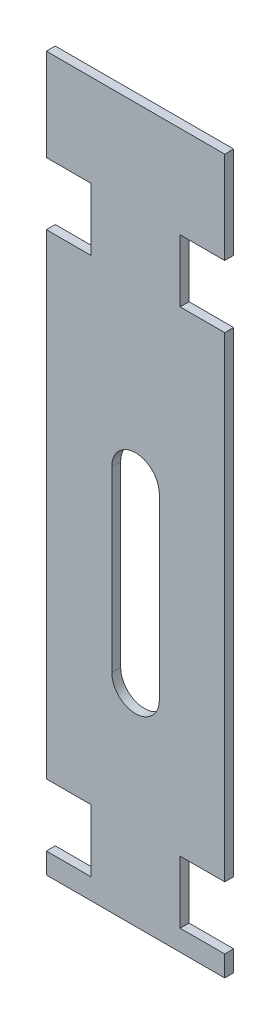
SolidWorks part; units mm, degrees
ref_plane "前视基准面" through (0, 0, 0) normal (0, 0, 1) x (1, 0, 0)
ref_plane "上视基准面" through (0, 0, 0) normal (0, 1, 0) x (1, 0, 0)
ref_plane "右视基准面" through (0, 0, 0) normal (1, 0, 0) x (0, 0, -1)
other "Configuration Table"
sketch "草图1" plane through (0, 0, 0) normal (0, 0, 1) x (1, 0, 0)
  line L1 (0, 0) -> (60, 0)
  line L2 (0, 0) -> (0, 240)
  line L3 (0, 240) -> (60, 240)
  line L4 (60, 0) -> (60, 240)
  dimension "D1" = 60
  dimension "D2" = 240
extrude "凸台-拉伸1" add sketch "草图1" along normal blind 3
sketch "草图4" plane through (0, 0, 0) normal (0, 0, -1) x (-1, 0, 0)
  line L0 (-60, 7) -> (-45, 7)
  line L1 (-60, 0) -> (-60, 240) construction
  line L2 (-45, 7) -> (-45, 28)
  line L3 (-45, 28) -> (-60, 28)
  line L4 (0, 0) -> (-60, 0) construction
  line L5 (-60, 28) -> (-60, 7)
  line L6 (0, 240) -> (0, 0) construction
  line L7 (0, 28) -> (-15, 28)
  line L8 (0, 28) -> (0, 7)
  line L9 (0, 7) -> (-15, 7)
  line L10 (-15, 28) -> (-15, 7)
  line L11 (-60, 216) -> (0, 216) construction
  line L12 (-60, 240) -> (0, 240) construction
  line L13 (0, 209) -> (-15, 209)
  line L14 (-15, 209) -> (-15, 188)
  line L15 (-15, 188) -> (0, 188)
  line L16 (-60, 209) -> (-45, 209)
  line L17 (-45, 209) -> (-45, 188)
  line L18 (-45, 188) -> (-60, 188)
  line L19 (-60, 188) -> (-60, 209)
  line L20 (0, 209) -> (0, 188)
  line L21 (-30, 0) -> (-30, 216) construction
  line L22 (-30, 130) -> (-30, 70) construction
  line L23 (-22, 130) -> (-22, 70)
  line L24 (-38, 130) -> (-38, 70)
  arc A0 (-22, 130) -> (-38, 130) centre (-30, 130) ccw
  arc A1 (-38, 70) -> (-22, 70) centre (-30, 70) ccw
  point P30 (-30, 100)
  dimension "D7" = 8
  dimension "D1" = 7
  dimension "D2" = 21
  dimension "D3" = 15
  dimension "D4" = 24
  dimension "D5" = 21
  dimension "D6" = 7
  dimension "D8" = 60
  dimension "D9" = 100
extrude "切除-拉伸1" cut sketch "草图4" against normal blind 3
